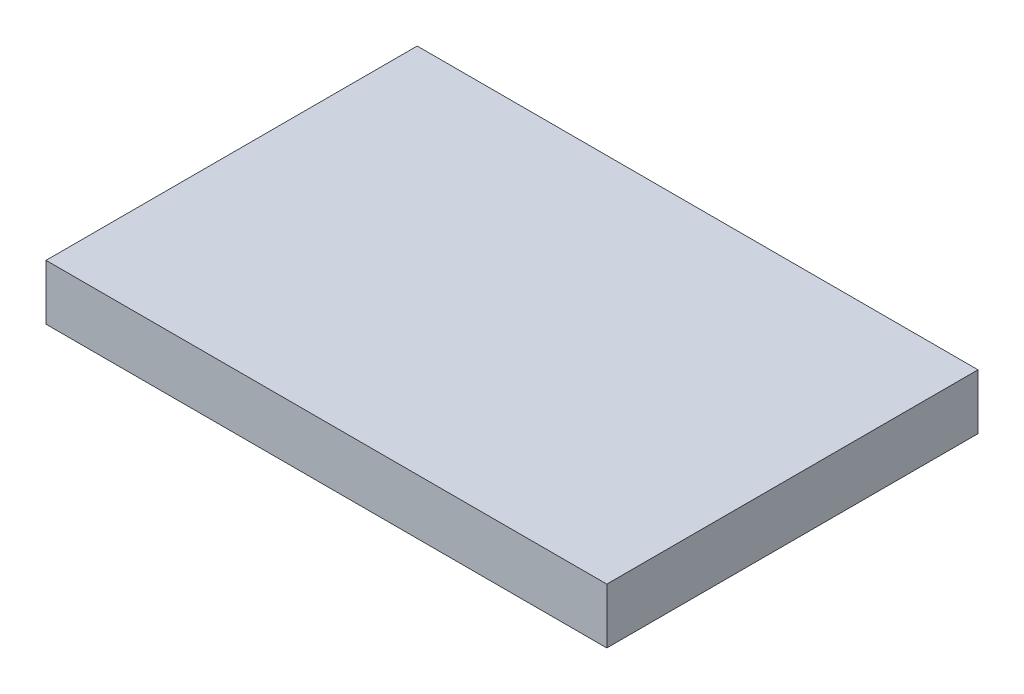
SolidWorks part; units mm, degrees
ref_plane "前视基准面" through (0, 0, 0) normal (0, 0, 1) x (1, 0, 0)
ref_plane "上视基准面" through (0, 0, 0) normal (0, 1, 0) x (1, 0, 0)
ref_plane "右视基准面" through (0, 0, 0) normal (1, 0, 0) x (0, 0, -1)
other "Configuration Table"
sketch "草图1" plane through (0, 0, 0) normal (0, 1, 0) x (1, 0, 0)
  line L1 (0, 0) -> (101.3603, 0)
  line L2 (0, 0) -> (0, -67.0917)
  line L3 (0, -67.0917) -> (101.3603, -67.0917)
  line L4 (101.3603, 0) -> (101.3603, -67.0917)
extrude "凸台-拉伸1" add sketch "草图1" along normal blind 10
